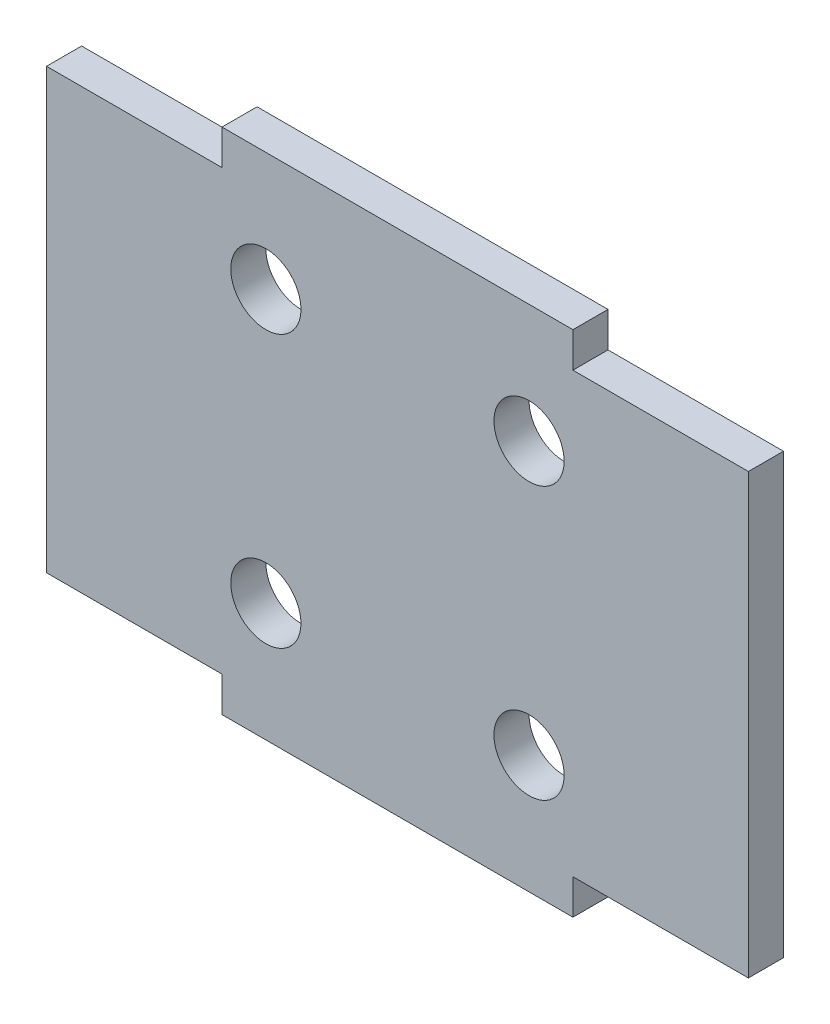
SolidWorks part; units mm, degrees
ref_plane "Front Plane" through (0, 0, 0) normal (0, 0, 1) x (1, 0, 0)
ref_plane "Top Plane" through (0, 0, 0) normal (0, 1, 0) x (1, 0, 0)
ref_plane "Right Plane" through (0, 0, 0) normal (1, 0, 0) x (0, 0, -1)
sketch "Sketch1" plane through (0, 0, 0) normal (0, 0, 1) x (1, 0, 0)
  line L0 (-40, 0) -> (64.7716, 0) construction
  line L1 (-20, 29) -> (20, 29)
  line L2 (-40, 25) -> (-40, -25)
  line L3 (-20, -29) -> (20, -29)
  line L4 (40, 25) -> (40, -25)
  line L5 (-33.6, 25) -> (33.6, -25) construction
  line L6 (-33.6, -25) -> (33.6, 25) construction
  line L7 (0, -10.0508) -> (0, 10.0508) construction
  line L8 (-33.6, 25) -> (33.6, -25) construction
  line L9 (-33.6, -25) -> (40, 21) construction
  line L10 (-20, -29) -> (-20, -25)
  line L13 (-40, 25) -> (-20, 25)
  line L14 (-20, 29) -> (-20, 25)
  line L15 (-40, -25) -> (-20, -25)
  line L20 (40, -25) -> (20, -25)
  line L21 (20, -29) -> (20, -25)
  line L22 (20, 29) -> (20, 25)
  line L23 (40, 25) -> (20, 25)
  circle A0 centre (15, 15.5) radius 4
  circle A1 centre (-15, 15.5) radius 4
  circle A2 centre (-15, -15.5) radius 4
  circle A3 centre (15, -15.5) radius 4
  point P0 (0, 0)
  point P3 (0, 0)
  point P15 (0, 0)
  point P33 (0, 0)
  dimension "D5" = 8
  dimension "D1" = 50
  dimension "D2" = 31
  dimension "D4" = 15
  dimension "D6" = 20
  dimension "D7" = 4
extrude "Boss-Extrude1" add sketch "Sketch1" along normal blind 4
